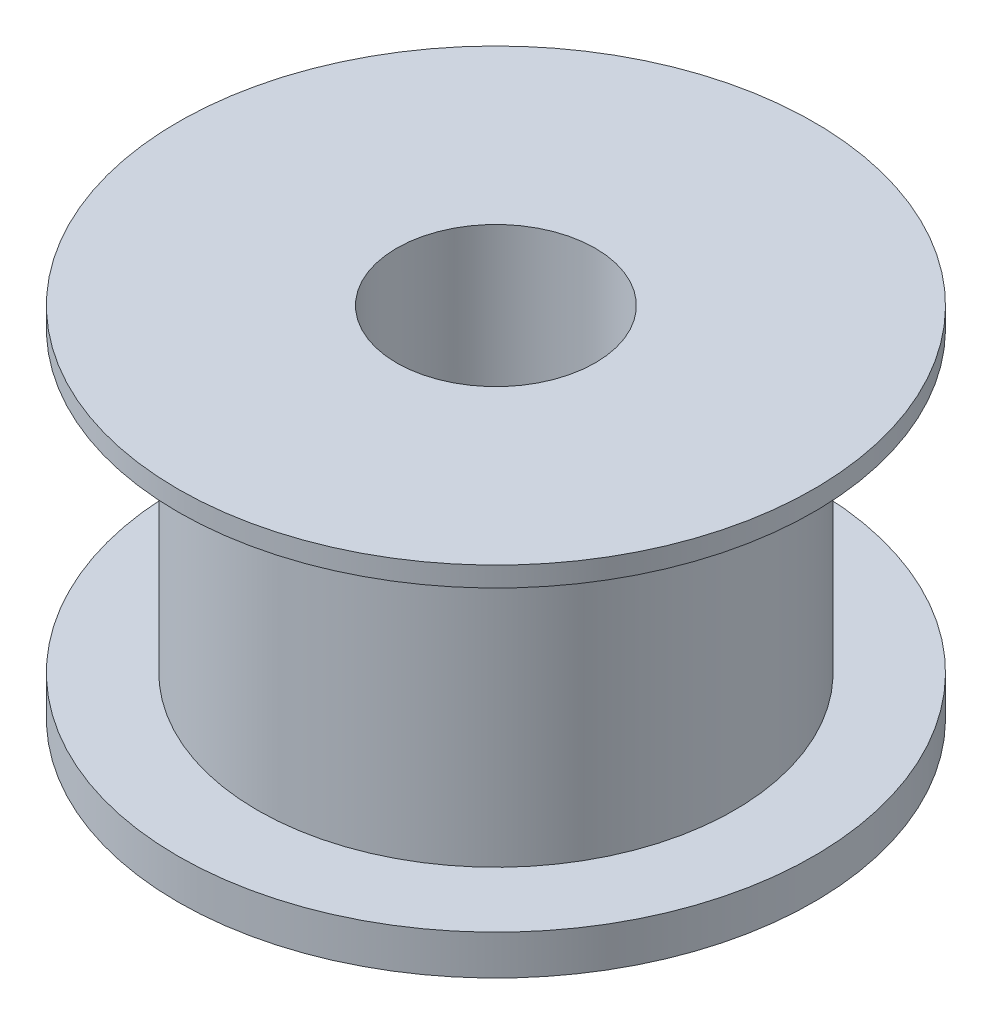
SolidWorks part; units mm, degrees
ref_plane "前视基准面" through (0, 0, 0) normal (0, 0, 1) x (1, 0, 0)
ref_plane "上视基准面" through (0, 0, 0) normal (0, 1, 0) x (1, 0, 0)
ref_plane "右视基准面" through (0, 0, 0) normal (1, 0, 0) x (0, 0, -1)
sketch "草图1" plane through (0, 0, 0) normal (0, 1, 0) x (1, 0, 0)
  circle A0 centre (0, 0) radius 8
  dimension "D1" = 16
extrude "凸台-拉伸1" add sketch "草图1" along normal blind 1
sketch "草图2" plane through (0, 1, 0) normal (0, 1, 0) x (1, 0, 0)
  circle A0 centre (0, 0) radius 6
  dimension "D1" = 12
extrude "凸台-拉伸2" add sketch "草图2" along normal blind 7.5
sketch "草图3" plane through (0, 8.5, 0) normal (0, 1, 0) x (1, 0, 0)
  circle A0 centre (0, 0) radius 8
  dimension "D1" = 16
extrude "凸台-拉伸3" add sketch "草图3" along normal blind 0.5
sketch "草图4" plane through (0, 0, 0) normal (0, -1, 0) x (1, 0, 0)
  circle A0 centre (0, 0) radius 2.5
  dimension "D1" = 5
extrude "切除-拉伸1" cut sketch "草图4" against normal up to next
